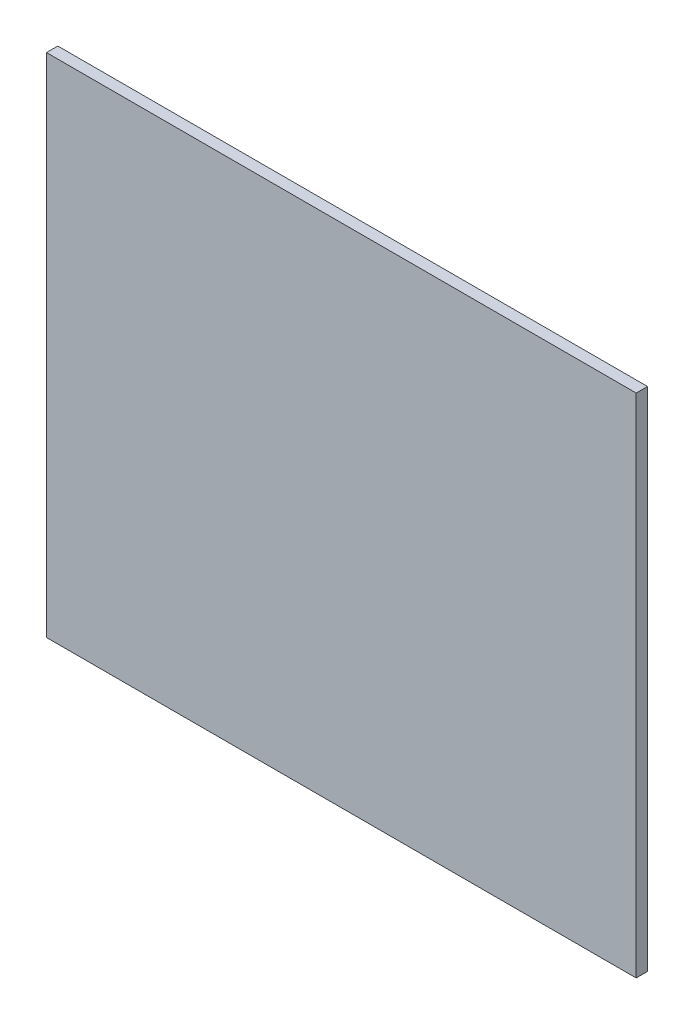
SolidWorks part; units mm, degrees
material "Chapa F.F 1020 - 1,5 mm"
ref_plane "Plano frontal" through (0, 0, 0) normal (0, 0, 1) x (1, 0, 0)
ref_plane "Plano superior" through (0, 0, 0) normal (0, 1, 0) x (1, 0, 0)
ref_plane "Plano direito" through (0, 0, 0) normal (1, 0, 0) x (0, 0, -1)
sketch "Esboço1" plane through (0, 0, 0) normal (0, 0, 1) x (1, 0, 0)
  line L1 (-39, -33.5) -> (39, -33.5)
  line L2 (-39, -33.5) -> (-39, 33.5)
  line L3 (-39, 33.5) -> (39, 33.5)
  line L4 (39, -33.5) -> (39, 33.5)
  line L5 (-39, -33.5) -> (39, 33.5) construction
  line L6 (-39, 33.5) -> (39, -33.5) construction
  point P0 (0, 0)
  dimension "D1" = 78
  dimension "D2" = 67
extrude "Ressalto-extrusão1" add sketch "Esboço1" along normal blind 1.5
